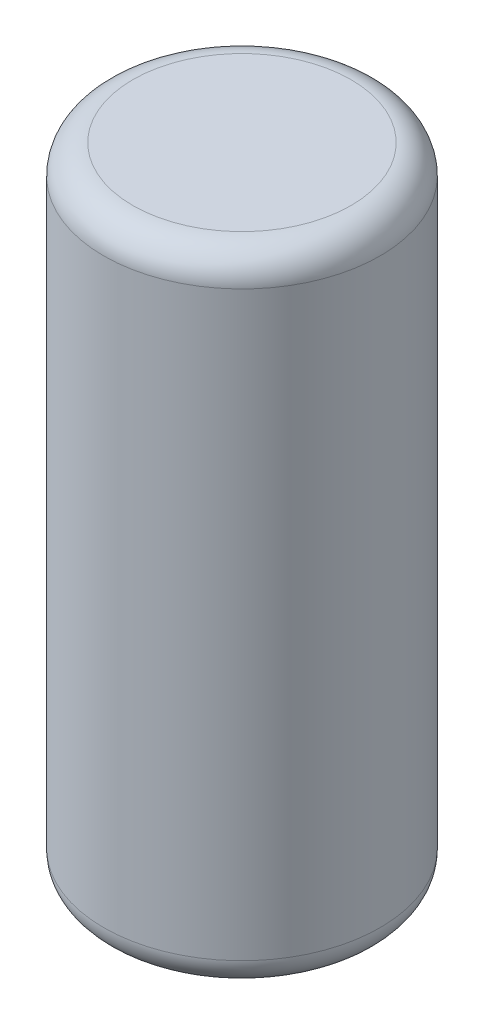
SolidWorks part; units mm, degrees
ref_plane "前视基准面" through (0, 0, 0) normal (0, 0, 1) x (1, 0, 0)
ref_plane "上视基准面" through (0, 0, 0) normal (0, 1, 0) x (1, 0, 0)
ref_plane "右视基准面" through (0, 0, 0) normal (1, 0, 0) x (0, 0, -1)
other "Configuration Table"
sketch "草图1" plane through (0, 0, 0) normal (0, 1, 0) x (1, 0, 0)
  circle A0 centre (0, 0) radius 4.75
  dimension "D1" = 9.5
extrude "凸台-拉伸1" add sketch "草图1" along normal blind 22
fillet "圆角1" radius 1 2 edges at (0, 0, 4.75) (0, 22, 4.75)
